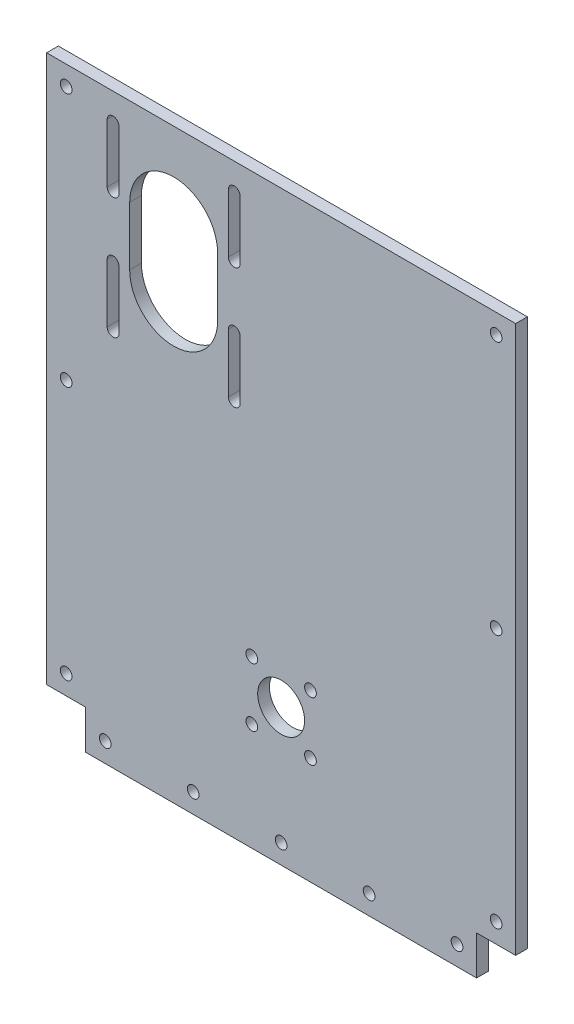
SolidWorks part; units mm, degrees
ref_plane "Plan de face" through (0, 0, 0) normal (0, 0, 1) x (1, 0, 0)
ref_plane "Plan de dessus" through (0, 0, 0) normal (0, 1, 0) x (1, 0, 0)
ref_plane "Plan de droite" through (0, 0, 0) normal (1, 0, 0) x (0, 0, -1)
sketch "Esquisse1" plane through (0, 0, 0) normal (0, 0, 1) x (1, 0, 0)
  line L0 (-27.5, 37.5) -> (-27.5, 52.5) construction
  line L1 (60, -75) -> (-60, -75)
  line L2 (60, -75) -> (60, 75)
  line L3 (60, 75) -> (-60, 75)
  line L4 (-60, -75) -> (-60, 75)
  line L5 (60, -75) -> (-60, 75) construction
  line L6 (60, 75) -> (-60, -75) construction
  line L9 (60, -65) -> (50, -65)
  line L10 (50, -75) -> (50, -65)
  line L13 (-60, -65) -> (-50, -65)
  line L14 (-50, -75) -> (-50, -65)
  line L15 (-38.75, 37.5) -> (-38.75, 52.5)
  line L16 (-16.25, 37.5) -> (-16.25, 52.5)
  line L17 (-43, 53) -> (-43, 68) construction
  line L18 (-44.5, 53) -> (-44.5, 68)
  line L19 (-41.5, 53) -> (-41.5, 68)
  line L20 (-43, 22) -> (-43, 37) construction
  line L21 (-44.5, 22) -> (-44.5, 37)
  line L22 (-41.5, 22) -> (-41.5, 37)
  line L24 (-27.5, 63.75) -> (-27.5, 26.25) construction
  line L27 (-12, 22) -> (-12, 37) construction
  line L30 (-10.5, 22) -> (-10.5, 37)
  line L31 (-13.5, 22) -> (-13.5, 37)
  line L32 (-12, 53) -> (-12, 68) construction
  line L33 (-10.5, 53) -> (-10.5, 68)
  line L34 (-13.5, 53) -> (-13.5, 68)
  arc A0 (-38.75, 37.5) -> (-16.25, 37.5) centre (-27.5, 37.5) ccw
  arc A1 (-16.25, 52.5) -> (-38.75, 52.5) centre (-27.5, 52.5) ccw
  arc A2 (-44.5, 53) -> (-41.5, 53) centre (-43, 53) ccw
  arc A3 (-41.5, 68) -> (-44.5, 68) centre (-43, 68) ccw
  arc A4 (-44.5, 22) -> (-41.5, 22) centre (-43, 22) ccw
  arc A5 (-41.5, 37) -> (-44.5, 37) centre (-43, 37) ccw
  arc A10 (-10.5, 22) -> (-13.5, 22) centre (-12, 22) cw
  arc A11 (-13.5, 37) -> (-10.5, 37) centre (-12, 37) cw
  arc A12 (-10.5, 53) -> (-13.5, 53) centre (-12, 53) cw
  arc A13 (-13.5, 68) -> (-10.5, 68) centre (-12, 68) cw
  point P0 (0, 0)
  point P14 (-27.5, 45)
  point P21 (-43, 60.5)
  point P28 (-43, 29.5)
  point P37 (-12, 29.5)
  point P44 (-12, 60.5)
  dimension "D1" = 10
  dimension "D2" = 10
  dimension "D3" = 150
  dimension "D4" = 120
  dimension "D5" = 32.5
  dimension "D6" = 15.5
  dimension "D7" = 22.5
  dimension "D8" = 3
  dimension "D9" = 15.5
  dimension "D10" = 15
  dimension "D11" = 3
  dimension "D12" = 31
extrude "Boss.-Extru.1" add sketch "Esquisse1" along normal blind 3 contours L14 L1 L10 L9 L2 L3 L4 L13 A5 L22 A4 L21 A3 L19 A2 L18 A1 L16 A0 L15 L31 A11 L30 A10 L34 A13 L33 A12
sketch "Esquisse2" plane through (0, 0, 3) normal (0, 0, 1) x (1, 0, 0)
  line L0 (-55, 75) -> (-55, -65) construction
  line L1 (60, 75) -> (-60, 75) construction
  line L2 (60, -65) -> (50, -65) construction
  line L3 (50, -70) -> (-50, -70) construction
  line L4 (50, -75) -> (50, -65) construction
  line L5 (-50, -75) -> (-50, -65) construction
  line L6 (0, 75) -> (0, -75) construction
  line L7 (50, -75) -> (-50, -75) construction
  circle A0 centre (45, -70) radius 1.5
  circle A3 centre (-55, -60) radius 1.5
  circle A4 centre (-55, 5) radius 1.5
  circle A5 centre (-55, 70) radius 1.5
  circle A9 centre (22.5, -70) radius 1.5
  circle A10 centre (0, -70) radius 1.5
  circle A11 centre (-22.5, -70) radius 1.5
  circle A12 centre (-45, -70) radius 1.5
  circle A13 centre (55, -60) radius 1.5
  circle A14 centre (55, 5) radius 1.5
  circle A15 centre (55, 70) radius 1.5
  dimension "D2" = 3
  dimension "D6" = 3
  dimension "D1" = 5
  dimension "D3" = 5
  dimension "D5" = 5
  dimension "D7" = 5
  dimension "D4" = 5
  dimension "D8" = 3
extrude "Enlèv. mat.-Extru.2" cut sketch "Esquisse2" against normal blind 3
sketch "Esquisse3" plane through (0, 0, 3) normal (0, 0, 1) x (1, 0, 0)
  line L3 (50, -75) -> (-50, -75) construction
  line L4 (0, 75) -> (0, -75) construction
  line L5 (60, 75) -> (-60, 75) construction
  line L6 (-7.5, -32.5) -> (7.5, -32.5) construction
  line L7 (7.5, -52.5) -> (-7.5, -52.5) construction
  line L8 (12.5, -47.5) -> (12.5, -32.5) construction
  line L9 (7.5, -27.5) -> (-7.5, -27.5) construction
  line L10 (-12.5, -47.5) -> (-12.5, -32.5) construction
  line L11 (12.5, -52.5) -> (-12.5, -27.5) construction
  line L12 (12.5, -27.5) -> (-12.5, -52.5) construction
  line L13 (-7.5, -32.5) -> (-7.5, -47.5) construction
  circle A0 centre (0, -40) radius 6
  arc A2 (-7.5, -52.5) -> (-12.5, -47.5) centre (-7.5, -47.5) cw construction
  arc A3 (7.5, -52.5) -> (12.5, -47.5) centre (7.5, -47.5) ccw construction
  arc A4 (12.5, -32.5) -> (7.5, -27.5) centre (7.5, -32.5) ccw construction
  arc A5 (-7.5, -27.5) -> (-12.5, -32.5) centre (-7.5, -32.5) ccw construction
  circle A6 centre (-7.5, -32.5) radius 1.5
  circle A7 centre (7.5, -32.5) radius 1.5
  circle A8 centre (7.5, -47.5) radius 1.5
  circle A9 centre (-7.5, -47.5) radius 1.5
  dimension "D1" = 12
  dimension "D2" = 35
  dimension "D3" = 25
  dimension "D4" = 5
  dimension "D5" = 3
  dimension "D6" = 2
  dimension "D7" = 2
extrude "Enlèv. mat.-Extru.3" cut sketch "Esquisse3" against normal blind 10
